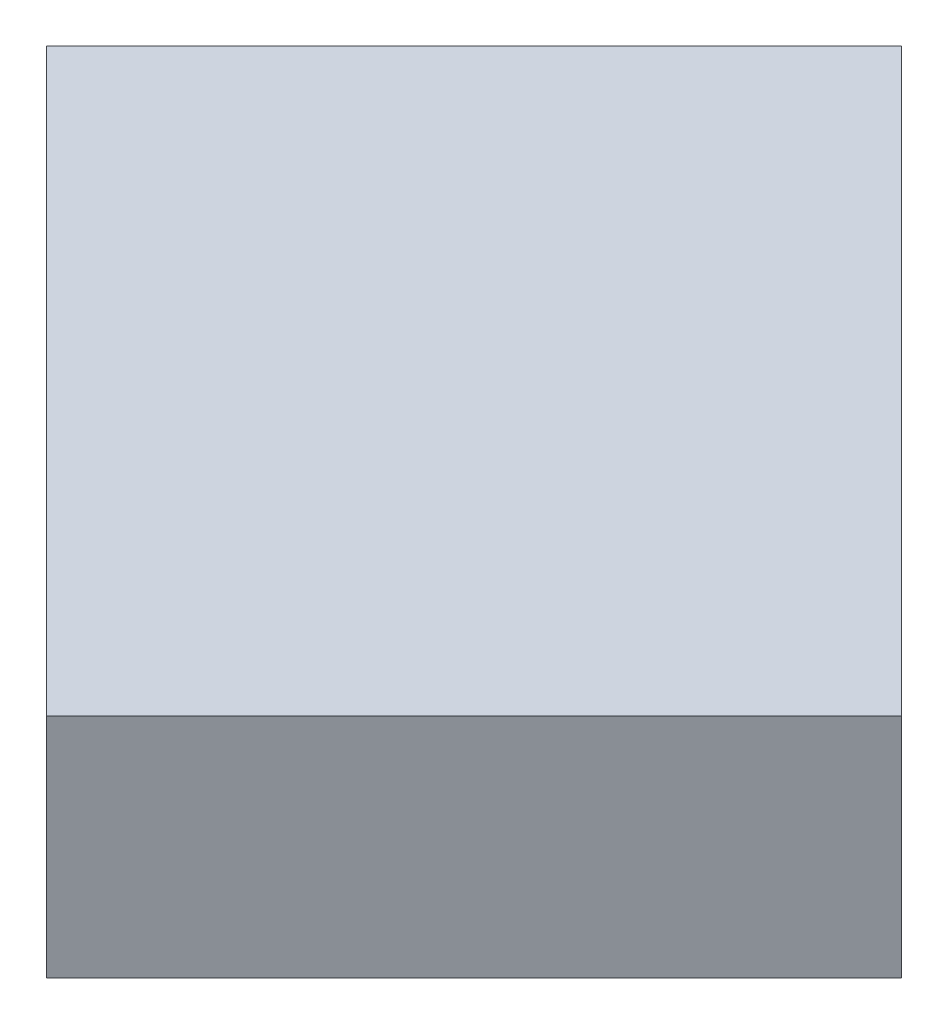
SolidWorks part; units mm, degrees
ref_plane "Front Plane" through (0, 0, 0) normal (0, 0, 1) x (1, 0, 0)
ref_plane "Top Plane" through (0, 0, 0) normal (0, 1, 0) x (1, 0, 0)
ref_plane "Right Plane" through (0, 0, 0) normal (1, 0, 0) x (0, 0, -1)
sketch "Sketch1" plane through (0, 0, 0) normal (0, 1, 0) x (1, 0, 0)
  line L0 (0, 0) -> (0, 32.866) construction
  line L1 (0, 0) -> (-41.0221, 0) construction
  line L2 (-2.2274, 14.7078) -> (14.7078, -2.2274)
  line L3 (-6.2402, -6.2402) -> (6.2402, 6.2402) construction
  line L4 (0, 0) -> (-30.445, 30.445) construction
  line L5 (-14.7078, 2.2274) -> (2.2274, -14.7078)
  line L6 (2.2274, -14.7078) -> (14.7078, -2.2274)
  line L7 (-14.7078, 2.2274) -> (-2.2274, 14.7078)
  line L8 (0, 0) -> (30.445, 30.445) construction
  line L9 (-8.4676, 8.4676) -> (8.4676, -8.4676) construction
  dimension "D1" = 23.95
  dimension "D2" = 17.65
extrude "Boss-Extrude1" add sketch "Sketch1" along normal blind 6.62
